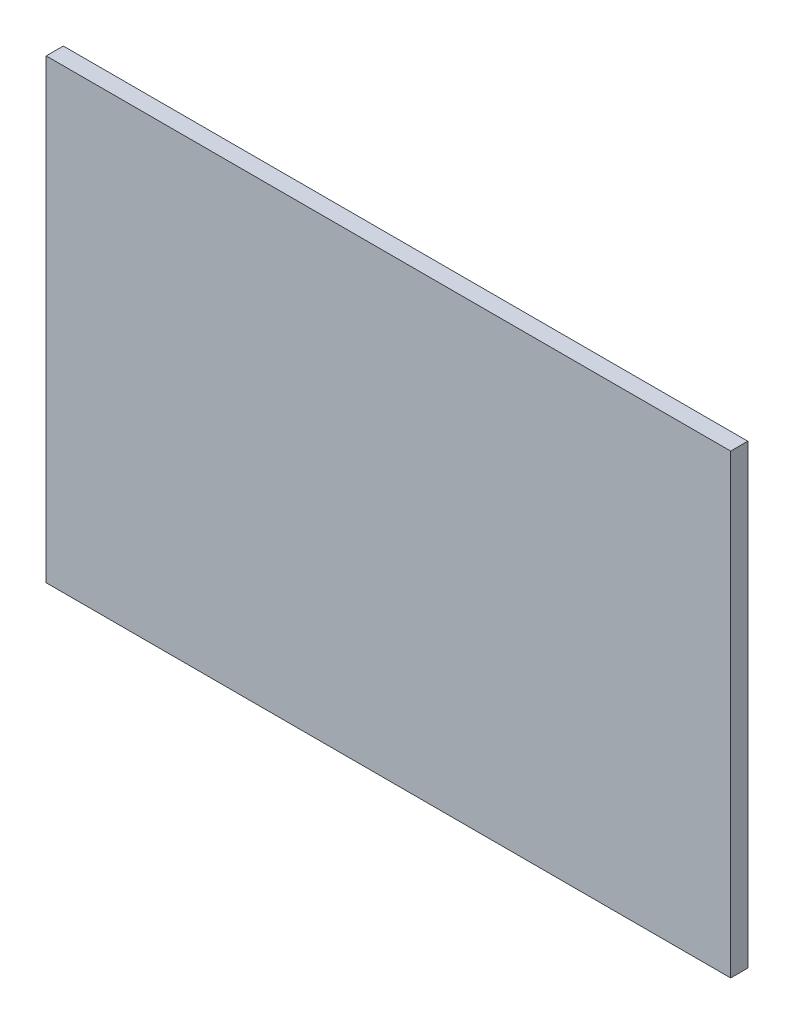
SolidWorks part; units mm, degrees
material "Beech"
ref_plane "Front Plane" through (0, 0, 0) normal (0, 0, 1) x (1, 0, 0)
ref_plane "Top Plane" through (0, 0, 0) normal (0, 1, 0) x (1, 0, 0)
ref_plane "Right Plane" through (0, 0, 0) normal (1, 0, 0) x (0, 0, -1)
sketch "Sketch1" plane through (0, 0, 0) normal (0, 0, 1) x (1, 0, 0)
  line L1 (300, -200) -> (-300, -200)
  line L2 (300, -200) -> (300, 200)
  line L3 (300, 200) -> (-300, 200)
  line L4 (-300, -200) -> (-300, 200)
  line L5 (300, -200) -> (-300, 200) construction
  line L6 (300, 200) -> (-300, -200) construction
  point P0 (0, 0)
  dimension "D1" = 600
  dimension "D2" = 400
extrude "Boss-Extrude1" add sketch "Sketch1" along normal blind 15
